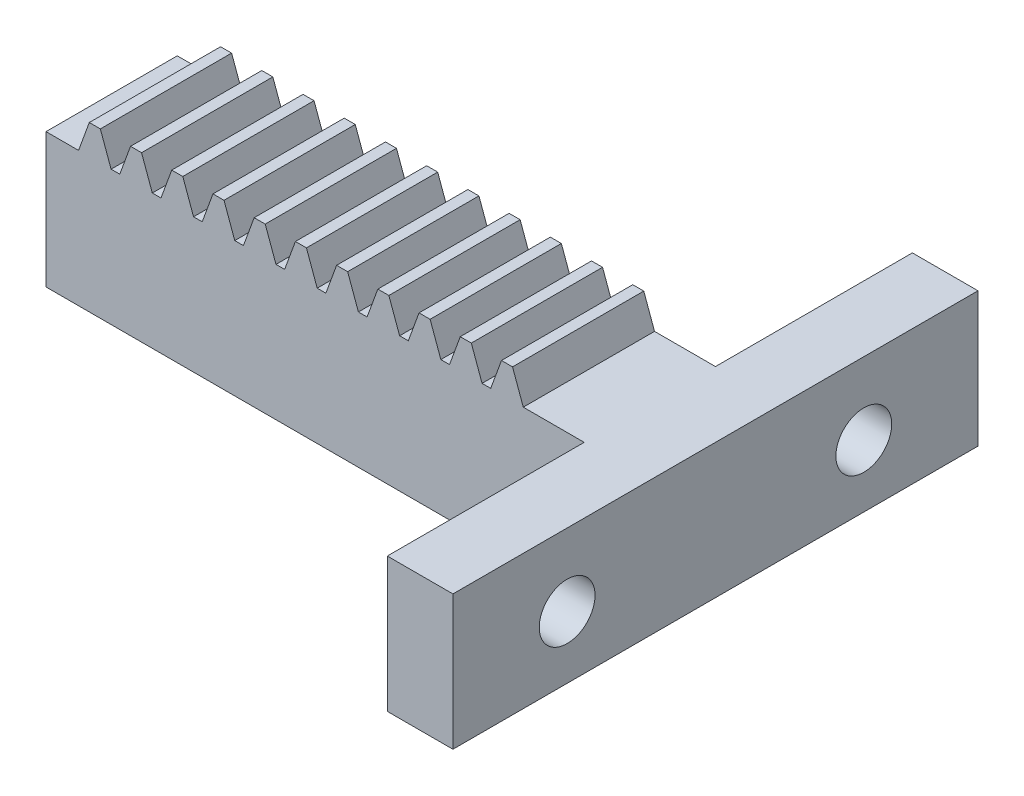
SolidWorks part; units mm, degrees
ref_plane "前视基准面" through (0, 0, 0) normal (0, 0, 1) x (1, 0, 0)
ref_plane "上视基准面" through (0, 0, 0) normal (0, 1, 0) x (1, 0, 0)
ref_plane "右视基准面" through (0, 0, 0) normal (1, 0, 0) x (0, 0, -1)
sketch "草图1" plane through (0, 0, 0) normal (0, 0, 1) x (1, 0, 0)
  line L1 (0, 0) -> (92, 0)
  line L2 (0, 0) -> (0, 20)
  line L3 (0, 20) -> (92, 20)
  line L4 (92, 0) -> (92, 20)
  dimension "H0" = 20
  dimension "L" = 92
extrude "凸台-拉伸1" add sketch "草图1" along normal blind 20
sketch "草图2" plane through (0, 0, 20) normal (0, 0, 1) x (1, 0, 0)
  line L0 (2, 20) -> (3.6379, 15.5)
  line L1 (92, 20) -> (0, 20) construction
  line L2 (3.6379, 15.5) -> (4.9596, 15.5)
  line L3 (4.9596, 15.5) -> (6.5975, 20)
  line L4 (6.5975, 20) -> (2, 20)
  line L5 (0, 18) -> (92, 18) construction
  line L6 (0, 20) -> (0, 0) construction
  line L7 (92, 0) -> (92, 20) construction
  line L9 (8.28, 20) -> (9.9179, 15.5) construction
  line L10 (9.9179, 15.5) -> (4.9596, 15.5) construction
  line L12 (8.28, 20) -> (6.5975, 20) construction
  point P12 (2.7279, 18)
  point P13 (5.8695, 18)
  point P14 (9.0079, 18)
  dimension "H" = 4.5
  dimension "H1" = 2
  dimension "A" = 2
  dimension "P" = 6.28
  dimension "E" = 3.1416
  dimension "D1" = 20
extrude "切除-拉伸1" cut sketch "草图2" against normal through all
pattern_linear "阵列(线性)1" count 14 spacing 6.28 along (1, 0, 0) of "切除-拉伸1"
sketch "草图3" plane through (0, 0, 20) normal (0, 0, 1) x (1, 0, 0)
  line L0 (2, 20) -> (0, 20)
  line L1 (0, 20) -> (0, 15.5)
  line L2 (0, 20) -> (0, 0) construction
  line L3 (0, 15.5) -> (3.6379, 15.5)
  line L4 (3.6379, 15.5) -> (2, 20)
  line L5 (74.0396, 15.5) -> (75.6775, 20)
  line L6 (75.6775, 20) -> (92, 20)
  line L7 (92, 20) -> (92, 15.5)
  line L8 (92, 0) -> (92, 20) construction
  line L9 (92, 15.5) -> (74.0396, 15.5)
extrude "切除-拉伸2" cut sketch "草图3" against normal through all
sketch "草图4" plane through (92, 0, 0) normal (1, 0, 0) x (0, 0, -1)
  line L4 (-20, 0) -> (-50, 0)
  line L5 (-50, 0) -> (-50, 15.5)
  line L6 (-50, 15.5) -> (-20, 15.5)
  line L7 (-20, 0) -> (-20, 15.5)
  line L8 (0, 15.5) -> (30, 15.5)
  line L9 (0, 0) -> (30, 0)
  line L10 (30, 0) -> (30, 15.5)
  line L11 (0, 0) -> (0, 15.5)
  line L12 (0, 15.5) -> (-20, 15.5) construction
  dimension "D2" = 30
  dimension "D3" = 30
extrude "凸台-拉伸2" add sketch "草图4" against normal blind 10
sketch "草图6" plane through (0, 0, 0) normal (0, -1, 0) x (1, 0, 0)
  line L0 (82, 0) -> (82, 20)
  line L8 (0, 0) -> (82, 0)
  line L9 (82, 0) -> (82, -30)
  line L10 (82, -30) -> (92, -30)
  line L11 (92, -30) -> (92, 50)
  line L12 (92, 50) -> (82, 50)
  line L13 (82, 50) -> (82, 20)
  line L14 (82, 20) -> (0, 20)
  line L15 (0, 20) -> (0, 0)
  line L17 (82, 0) -> (82, -30)
  line L18 (82, -30) -> (92, -30)
  line L19 (92, -30) -> (92, 50)
  line L20 (92, 50) -> (82, 50)
  line L21 (82, 50) -> (82, 20)
  dimension "D1" = 0
extrude "凸台-拉伸3" add sketch "草图6" along normal blind 5
sketch "草图9" plane through (92, 0, 0) normal (1, 0, 0) x (0, 0, -1)
  line L0 (-50, 4.5) -> (30, 4.5) construction
  line L1 (-50, 15.5) -> (-50, -5) construction
  line L2 (30, -5) -> (30, 15.5) construction
  line L3 (30, -5) -> (-50, -5) construction
  line L4 (-10, -5) -> (-10, 15.5) construction
  line L5 (30, 15.5) -> (-50, 15.5) construction
  circle A0 centre (-32.6, 4.5) radius 4.25
  circle A1 centre (12.6, 4.5) radius 4.25
  dimension "D2" = 8.5
  dimension "D3" = 45.2
  dimension "D1" = 9.5
extrude "切除-拉伸6" cut sketch "草图9" against normal through all
sketch "草图11" plane through (0, 0, 0) normal (-1, 0, 0) x (0, 0, 1)
  line L0 (0, 0) -> (0, -5)
  line L1 (50, -5) -> (-30, -5) construction
  line L2 (0, -5) -> (20, -5)
  line L3 (20, -5) -> (20, 0)
  line L4 (20, 0) -> (0, 0)
extrude "凸台-拉伸4" add sketch "草图11" against normal up to surface (82 mm away) up to face at (82, 4.5, 36.85)
sketch "草图12" plane through (0, -5, 0) normal (0, -1, 0) x (1, 0, 0)
  line L0 (0, 10) -> (92, 10) construction
  line L1 (0, 0) -> (0, 20) construction
  line L2 (92, -30) -> (92, 50) construction
  circle A0 centre (7.5, 10) radius 1.75
  circle A1 centre (27.5, 10) radius 1.75
  circle A2 centre (47.5, 10) radius 1.75
  dimension "D2" = 20
  dimension "D3" = 20
  dimension "D4" = 3.5
  dimension "D1" = 7.5
extrude "切除-拉伸7" cut sketch "草图12" against normal blind 3
equation "\"D3@阵列(线性)1\"= \"P@草图2\""
